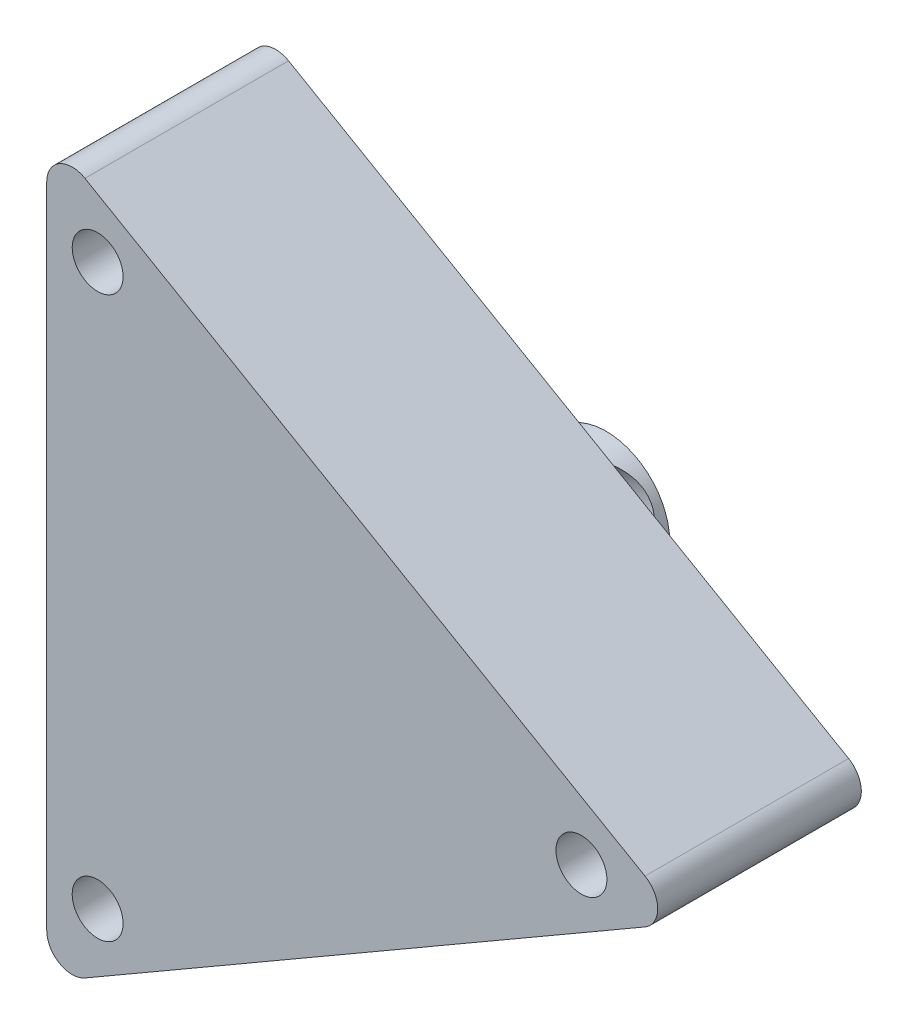
SolidWorks part; units mm, degrees
ref_plane "Ön Düzlem" through (0, 0, 0) normal (0, 0, 1) x (1, 0, 0)
ref_plane "Üst Düzlem" through (0, 0, 0) normal (0, 1, 0) x (1, 0, 0)
ref_plane "Sağ Düzlem" through (0, 0, 0) normal (1, 0, 0) x (0, 0, -1)
ref_plane "Düzlem1" through (0, 0, 0) normal (0, 0, -1) x (-1, 0, 0)
sketch "Çizim1" plane through (0, 0, 0) normal (0, 0, -1) x (-1, 0, 0)
  line L0 (24.1447, 27.2093) -> (-19.8635, 1.7309)
  line L1 (-19.8635, -1.7309) -> (24.1447, -27.2093)
  line L2 (27.1468, -25.4785) -> (27.1468, 25.4785)
  arc A0 (27.1468, 25.4785) -> (24.1447, 27.2093) centre (25.1468, 25.4785) ccw
  arc A1 (-19.8635, 1.7309) -> (-19.8635, -1.7309) centre (-18.8615, 0) ccw
  arc A2 (24.1447, -27.2093) -> (27.1468, -25.4785) centre (25.1468, -25.4785) ccw
extrude "Yükseklik-Ekstrüzyon1" add sketch "Çizim1" against normal blind 16
ref_plane "Düzlem2" through (0, -0.5215, 0) normal (0, 1, 0) x (1, 0, 0)
sketch "Çizim2" plane through (0, -0.5215, 0) normal (0, 1, 0) x (1, 0, 0)
  line L0 (-4.1935, 10) -> (-9.1935, 10)
  line L1 (-9.1935, 10) -> (-9.1935, 0)
  line L2 (-9.1935, 0) -> (-4.1935, 0)
  line L3 (-4.1935, 0) -> (-4.1935, 10)
  line L4 (-9.1935, 10) -> (-9.1935, 0) construction
revolve "Döndür1" add sketch "Çizim2" angle 360 about L4
hole_wizard "Ø4.0 (4) Çap Delik1" positions "Çizim4" profile "Çizim3" hole size "Ø4.0" standard "ANSI Metric"
sketch "Çizim4" plane through (0, 0, 0) normal (0, 0, -1) x (-1, 0, 0)
  point P0 (23.1468, -22.0096)
  point P1 (-14.8697, 0)
  point P2 (23.1468, 22.0096)
sketch "Çizim3" plane through (-23.1468, -22.0096, 0) normal (1, 0, 0) x (0, 1, 0)
  line L0 (0, 0) -> (0, 16)
  line L1 (0, 16) -> (2, 16)
  line L2 (2, 16) -> (2, 0)
  line L5 (2, 0) -> (0, 0)
  line L11 (0, -6.35) -> (0, 107.95) construction
  dimension "Thru Hole Dia." = 4
  dimension "Thru Hole Depth" = 16
ref_plane "Düzlem3" through (-2.7846, -1.6121, 0) normal (0.8654, 0.501, 0) x (0, 0, -1)
hole_wizard "M8 Boşluklu Delik1" positions "Çizim6" profile "Çizim5" hole size "M8" standard "ANSI Metric"
sketch "Çizim6" plane through (-2.7846, -1.6121, 0) normal (0.8654, 0.501, 0) x (0, 0, -1)
  point P0 (5, 4.4335)
sketch "Çizim5" plane through (-5.0059, 2.2248, -5) normal (0, 0, 1) x (-0.501, 0.8654, 0)
  line L0 (0, 0) -> (0, 34.0437)
  line L1 (0, 34.0437) -> (4.275, 34.0437)
  line L2 (4.275, 34.0437) -> (4.275, 0)
  line L5 (4.275, 0) -> (0, 0)
  line L11 (0, -6.35) -> (0, 107.95) construction
  dimension "Thru Hole Dia." = 8.55
  dimension "Thru Hole Depth" = 34.0437
